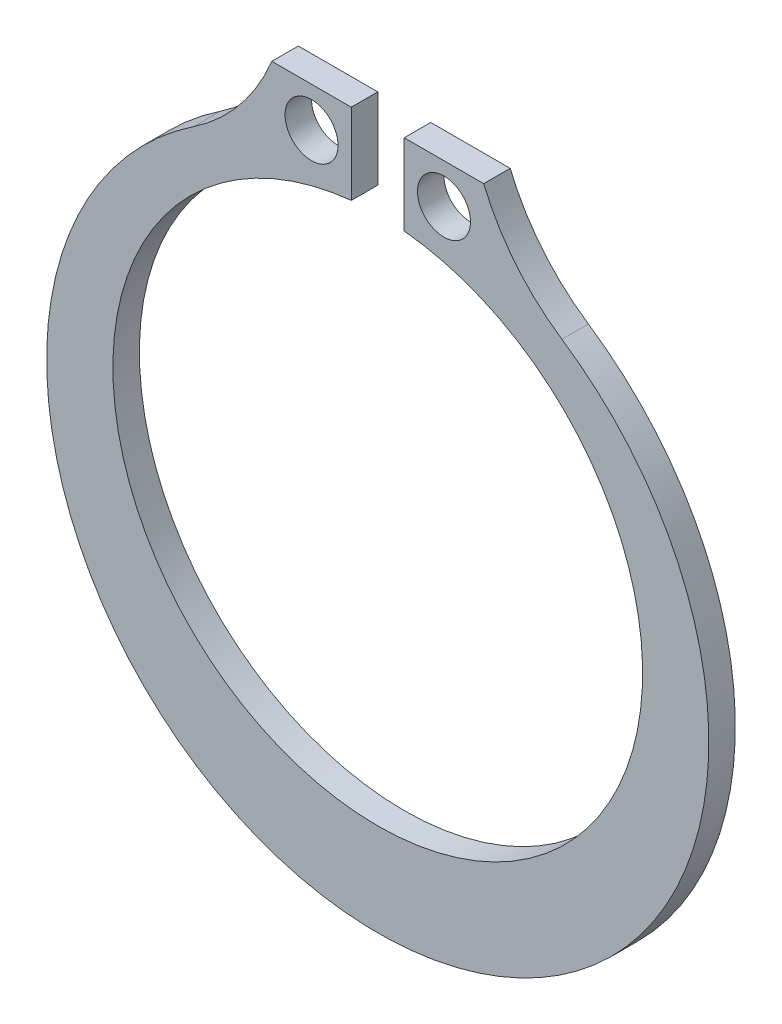
SolidWorks part; units mm, degrees
material "Alloy Steel"
ref_plane "Front Plane" through (0, 0, 0) normal (0, 0, 1) x (1, 0, 0)
ref_plane "Top Plane" through (0, 0, 0) normal (0, 1, 0) x (1, 0, 0)
ref_plane "Right Plane" through (0, 0, 0) normal (1, 0, 0) x (0, 0, -1)
sketch "Sketch1" plane through (0, 0, 0) normal (0, 0, 1) x (1, 0, 0)
  line L0 (0, 0) -> (0, 6.0682) construction
  line L1 (-4, 14) -> (-1, 14)
  line L2 (-1, 14) -> (-1, 10.9499)
  line L3 (1, 14) -> (1, 10.9499)
  line L4 (4, 14) -> (1, 14)
  arc A0 (-6.9519, 10.3885) -> (6.9519, 10.3885) centre (0, 0) ccw
  arc A1 (-1, 10.9499) -> (1, 10.9499) centre (0, 1) ccw
  arc A2 (-4, 14) -> (-6.9519, 10.3885) centre (-11.401, 17.0372) cw
  arc A3 (4, 14) -> (6.9519, 10.3885) centre (11.401, 17.0372) ccw
  circle A4 centre (-2.5, 12.5) radius 1
  circle A5 centre (2.5, 12.5) radius 1
  dimension "D1" = 1
  dimension "D4" = 20
  dimension "D5" = 25
  dimension "D6" = 8
  dimension "D8" = 2
  dimension "D2" = 8
  dimension "D3" = 13
  dimension "D7" = 2
  dimension "D9" = 1.5
  dimension "D10" = 1.5
extrude "Boss-Extrude1" add sketch "Sketch1" along normal blind 1
